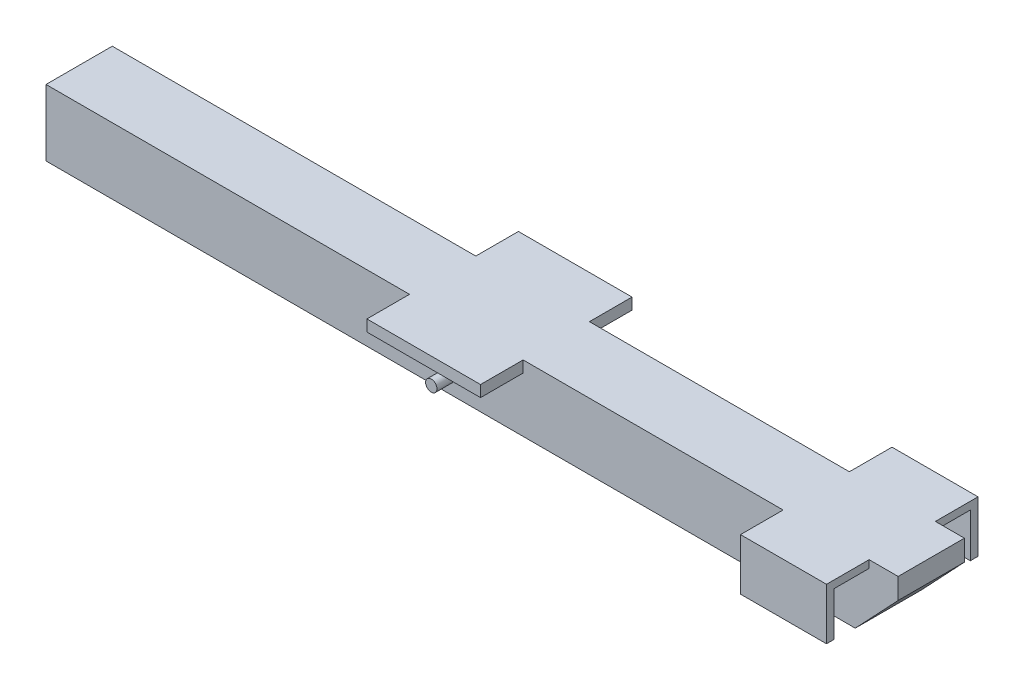
SolidWorks part; units mm, degrees
ref_plane "Front Plane" through (0, 0, 0) normal (0, 0, 1) x (1, 0, 0)
ref_plane "Top Plane" through (0, 0, 0) normal (0, 1, 0) x (1, 0, 0)
ref_plane "Right Plane" through (0, 0, 0) normal (1, 0, 0) x (0, 0, -1)
sketch "Sketch1" plane through (0, 0, 0) normal (0, 0, 1) x (1, 0, 0)
  line L1 (0, 0) -> (10854.7026, 0)
  line L3 (0, 889) -> (11430, 889)
  line L8 (11430, 889) -> (11430, 609.6)
  line L9 (11430, 609.6) -> (10854.7026, 0)
  line L11 (0, 889) -> (0, 0)
  point P3 (0, 0)
  point P5 (0, 0)
  point P6 (0, 0)
  point P10 (0, 0)
  point P11 (0, 0)
  point P12 (0, 0)
  point P13 (0, 0)
  dimension "D1" = 11430
  dimension "D2" = 889
  dimension "D3" = 279.4
  dimension "D4" = 838.2
extrude "Boss-Extrude1" add sketch "Sketch1" along normal blind 889
sketch "Sketch5" plane through (0, 0, 889) normal (0, 0, 1) x (1, 0, 0)
  line L0 (11430, 889) -> (0, 889) construction
  line L1 (11040.836, 889) -> (9887.1332, 889)
  line L2 (11040.836, 889) -> (11040.836, 197.2318)
  line L3 (11040.836, 197.2318) -> (9887.1332, 197.2318)
  line L4 (9887.1332, 889) -> (9887.1332, 197.2318)
  line L5 (10463.9846, 889) -> (10463.9846, 197.2318) construction
  line L6 (5637.9846, 889) -> (5637.9846, 736.6) construction
  line L7 (6399.9846, 889) -> (4875.9846, 889)
  line L8 (6399.9846, 889) -> (6399.9846, 736.6)
  line L9 (6399.9846, 736.6) -> (4875.9846, 736.6)
  line L10 (4875.9846, 889) -> (4875.9846, 736.6)
  line L11 (10854.7026, 0) -> (11430, 609.6) construction
  point P14 (7177.3723, 889)
  point P15 (10758.7723, 889)
  point P16 (10758.7723, 889)
  point P17 (0, 0)
  point P18 (0, 0)
  point P19 (0, 0)
  dimension "D1" = 4826
  dimension "D2" = 1524
  dimension "D3" = 152.4
  dimension "D4" = 1153.7028
  dimension "D5" = 691.7682
extrude "Boss-Extrude3" add sketch "Sketch5" along normal blind 571.5 and the other way blind 1460.5
sketch "Sketch6" plane through (11040.836, 0, 0) normal (1, 0, 0) x (0, 0, -1)
  line L0 (-889, 197.2318) -> (-1460.5, 197.2318) construction
  line L1 (-889, 197.2318) -> (-1357.4778, 197.2318)
  line L2 (-889, 197.2318) -> (-889, 787.4)
  line L3 (-889, 787.4) -> (-1357.4778, 787.4)
  line L4 (-1357.4778, 197.2318) -> (-1357.4778, 787.4)
  line L5 (-1460.5, 197.2318) -> (-1460.5, 889) construction
  line L6 (-889, 889) -> (-1460.5, 889) construction
  line L7 (-889, 197.2318) -> (0, 197.2318) construction
  line L8 (0, 197.2318) -> (0, 609.6) construction
  line L13 (-444.5, 197.2318) -> (-444.5, 889) construction
  line L14 (-889, 889) -> (0, 889) construction
  line L15 (0, 787.4) -> (468.4778, 787.4)
  line L16 (468.4778, 197.2318) -> (468.4778, 787.4)
  line L17 (0, 197.2318) -> (468.4778, 197.2318)
  line L18 (0, 197.2318) -> (0, 787.4)
  dimension "D1" = 103.0222
  dimension "D2" = 101.6
extrude "Cut-Extrude3" cut sketch "Sketch6" against normal up to next
sketch "Sketch7" plane through (0, 0, 889) normal (0, 0, 1) x (1, 0, 0)
  line L0 (4875.9846, 889) -> (6399.9846, 889) construction
  line L1 (5637.9846, 889) -> (5637.9846, 0) construction
  line L3 (6399.9846, 889) -> (4875.9846, 889) construction
  line L4 (0, 0) -> (10854.7026, 0) construction
  circle A0 centre (5637.9846, 444.5) radius 76.2
  point P8 (0, 0)
  point P10 (7177.3723, 444.5)
  point P12 (0, 0)
  point P13 (0, 0)
  point P14 (7470.5088, 429.3929)
  point P15 (0, 0)
  point P16 (0, 0)
  point P17 (7329.7723, 889)
  point P20 (0, 0)
extrude "Boss-Extrude4" add sketch "Sketch7" along normal blind 469.9 and the other way blind 1358.9
sketch "Sketch8" plane through (0, 0, 0) normal (-1, 0, 0) x (0, 0, 1)
  line L0 (0, 889) -> (0, 0) construction
  line L1 (76.2, 812.8) -> (812.8, 812.8)
  line L2 (76.2, 812.8) -> (76.2, 76.2)
  line L3 (76.2, 76.2) -> (812.8, 76.2)
  line L4 (812.8, 812.8) -> (812.8, 76.2)
  line L6 (889, 889) -> (889, 0) construction
  line L7 (889, 889) -> (0, 889) construction
  point P12 (444.5, 889)
  dimension "D1" = 76.2
  dimension "D3" = 76.2
  dimension "D4" = 76.2
extrude "Cut-Extrude4" cut sketch "Sketch8" against normal blind 10551.414
